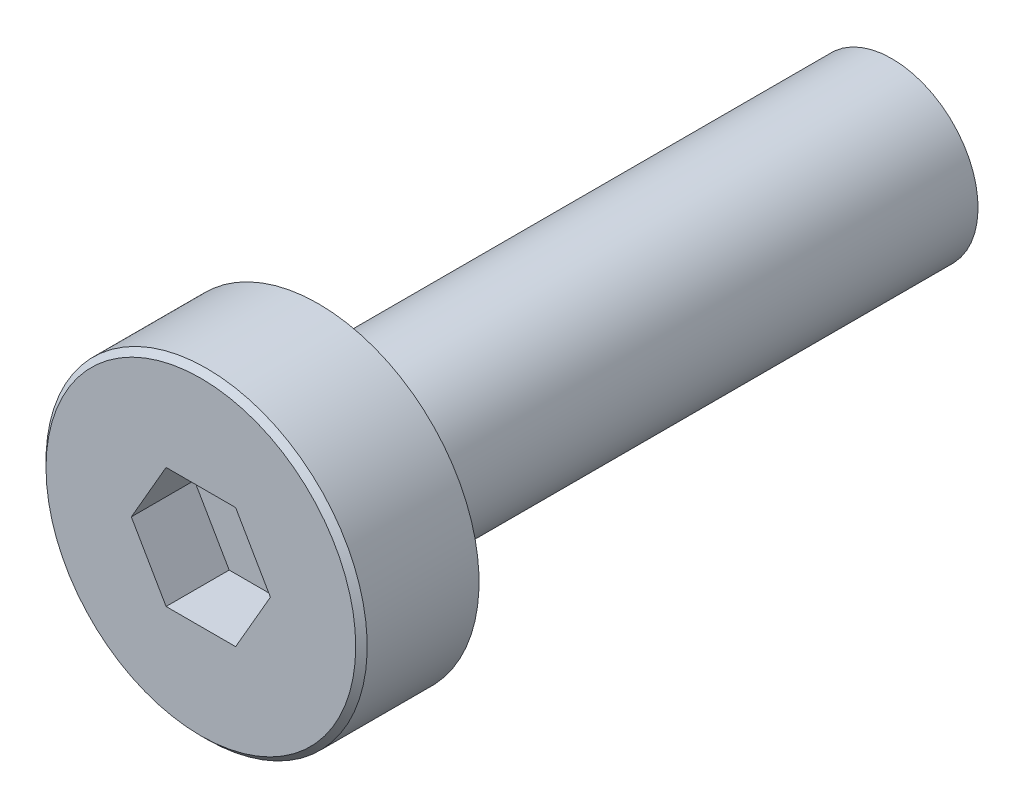
SolidWorks part; units mm, degrees
material "普通碳钢"
ref_plane "前视基准面" through (0, 0, 0) normal (0, 0, 1) x (1, 0, 0)
ref_plane "上视基准面" through (0, 0, 0) normal (0, 1, 0) x (1, 0, 0)
ref_plane "右视基准面" through (0, 0, 0) normal (1, 0, 0) x (0, 0, -1)
sketch "草图1" plane through (0, 0, 0) normal (1, 0, 0) x (0, 0, -1)
  line L0 (0, 0) -> (0, 2.8)
  line L1 (0, 2.8) -> (2.05, 2.8)
  line L2 (2.05, 2.8) -> (2.05, 1.5)
  line L3 (2.05, 1.5) -> (12.05, 1.5)
  line L4 (12.05, 1.5) -> (12.05, 0)
  line L5 (12.05, 0) -> (0, 0) construction
  line L6 (0, 0) -> (12.05, 0)
  dimension "D1" = 5.6
  dimension "D2" = 2.05
  dimension "D3" = 3
  dimension "D4" = 10
revolve "旋转1" add sketch "草图1" angle 360 about L5
sketch "草图2" plane through (0, 0, 0) normal (0, 0, 1) x (1, 0, 0)
  line L1 (0.6062, 1.05) -> (-0.6062, 1.05)
  line L2 (-0.6062, 1.05) -> (-1.2124, 0)
  line L3 (-1.2124, 0) -> (-0.6062, -1.05)
  line L4 (-0.6062, -1.05) -> (0.6062, -1.05)
  line L5 (0.6062, -1.05) -> (1.2124, 0)
  line L6 (1.2124, 0) -> (0.6062, 1.05)
  circle A0 centre (0, 0) radius 1.05 construction
  dimension "D1" = 2.1
extrude "切除-拉伸1" cut sketch "草图2" against normal blind 1.1
chamfer "装饰倒角" distance 0.1 angle 45 1 edges at (0, 2.8, 0)
